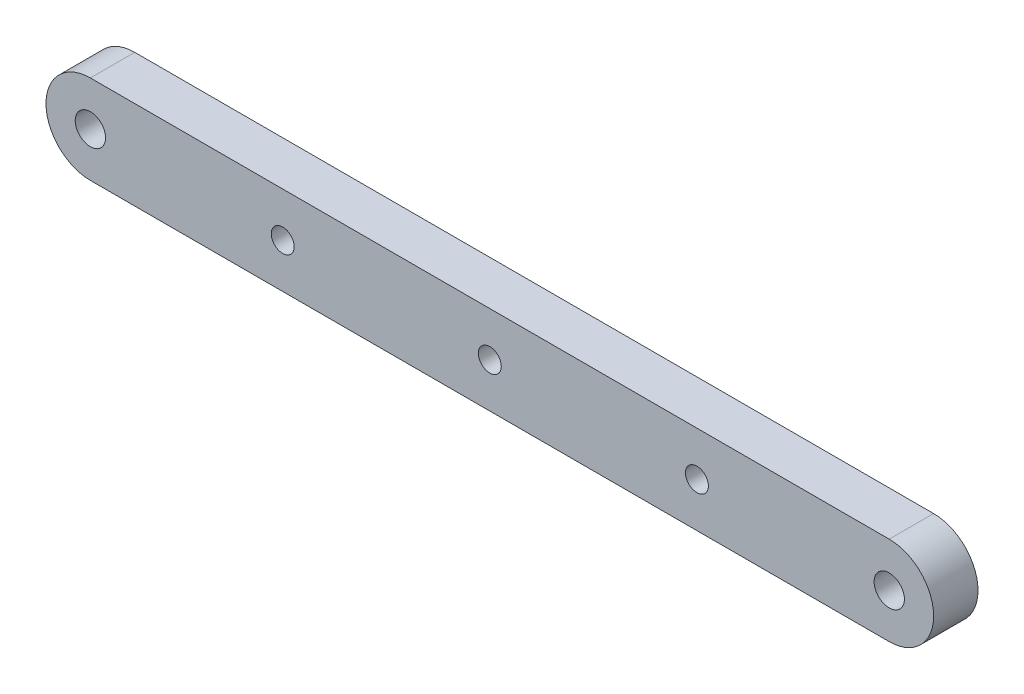
SolidWorks part; units mm, degrees
ref_plane "Płaszczyzna przednia" through (0, 0, 0) normal (0, 0, 1) x (1, 0, 0)
ref_plane "Płaszczyzna górna" through (0, 0, 0) normal (0, 1, 0) x (1, 0, 0)
ref_plane "Płaszczyzna prawa" through (0, 0, 0) normal (1, 0, 0) x (0, 0, -1)
sketch "Szkic1" plane through (0, 0, 0) normal (0, 0, 1) x (1, 0, 0)
  line L1 (135.2015, 17.704) -> (27.2015, 17.704)
  line L2 (135.2015, 5.704) -> (27.2015, 5.704)
  arc A0 (135.2015, 5.704) -> (135.2015, 17.704) centre (135.2015, 11.704) ccw
  arc A1 (27.2015, 17.704) -> (27.2015, 5.704) centre (27.2015, 11.704) ccw
  dimension "D2" = 6
  dimension "D3" = 6
  dimension "D4" = 108
  dimension "D5" = 6
  dimension "D1" = 12
  dimension "D6" = 6
extrude "Dodanie-wyciągnięcie1" add sketch "Szkic1" along normal blind 6
sketch "Szkic2" plane through (0, 0, 6) normal (0, 0, 1) x (1, 0, 0)
  circle A0 centre (135.2015, 11.704) radius 2.05
  circle A1 centre (27.2015, 11.704) radius 2.05
  arc A2 (27.2015, 17.704) -> (27.2015, 5.704) centre (27.2015, 11.704) ccw construction
  arc A3 (135.2015, 5.704) -> (135.2015, 17.704) centre (135.2015, 11.704) ccw construction
  dimension "D1" = 0
  dimension "D2" = 0
  dimension "D3" = 4.1
  dimension "D4" = 4.1
extrude "Wytnij-wyciągnięcie1" cut sketch "Szkic2" against normal blind 6
sketch "Szkic3" plane through (0, 0, 6) normal (0, 0, 1) x (1, 0, 0)
  circle A1 centre (53.2015, 11.704) radius 1.55
  circle A2 centre (53.2015, 11.704) radius 1.55
  circle A3 centre (81.2015, 11.704) radius 1.55
  circle A4 centre (81.2015, 11.704) radius 1.55
  circle A5 centre (109.2015, 11.704) radius 1.55
  circle A6 centre (109.2015, 11.704) radius 1.55
  dimension "D1" = 0
  dimension "D2" = 0
  dimension "D3" = 0
extrude "Wytnij-wyciągnięcie2" cut sketch "Szkic3" against normal blind 6
